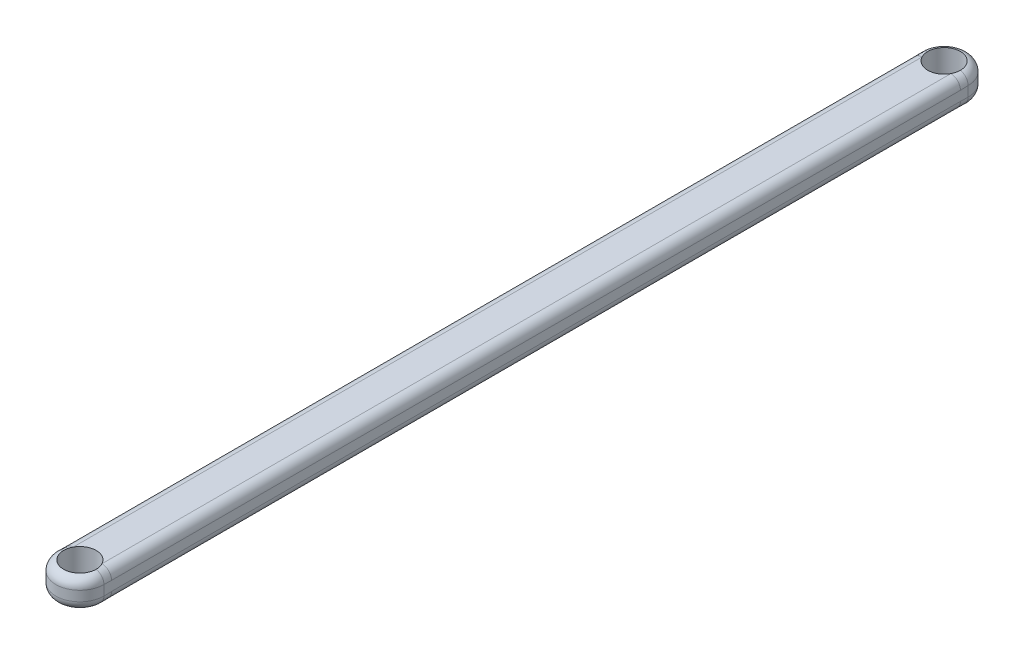
SolidWorks part; units mm, degrees
ref_plane "前视基准面" through (0, 0, 0) normal (0, 0, 1) x (1, 0, 0)
ref_plane "上视基准面" through (0, 0, 0) normal (0, 1, 0) x (1, 0, 0)
ref_plane "右视基准面" through (0, 0, 0) normal (1, 0, 0) x (0, 0, -1)
other "Configuration Table"
sketch "草图1" plane through (0, 0, 0) normal (0, 1, 0) x (1, 0, 0)
  line L0 (0, 0) -> (0, 90)
  line L1 (-2.5, 90) -> (-2.5, 0)
  line L2 (2.5, 0) -> (2.5, 90)
  circle A0 centre (0, 0) radius 2.5
  circle A1 centre (0, 90) radius 2.5
  dimension "D1" = 5
extrude "凸台-拉伸1" add sketch "草图1" along normal blind 3
sketch "草图2" plane through (0, 3, 0) normal (0, 1, 0) x (1, 0, 0)
  line L0 (2.5, 0) -> (2.5, 90) construction
  line L1 (-2.5, 90) -> (-2.5, 0) construction
  line L2 (0, 0) -> (0, 90) construction
  line L3 (2.5, 0) -> (2.5, 90)
  line L4 (-2.5, 90) -> (-2.5, 0)
  line L5 (0, 0) -> (0, 90)
  circle A0 centre (0, 0) radius 1.7
  circle A1 centre (0, 90) radius 2.5
  circle A2 centre (0, 90) radius 2.5
  circle A3 centre (0, 0) radius 2.5
  circle A4 centre (0, 0) radius 2.5
  circle A5 centre (0, 90) radius 1.7
  dimension "D1" = 0
  dimension "D2" = 0
extrude "切除-拉伸1" cut sketch "草图2" against normal up to next
fillet "圆角1" radius 1 4 edges at (-2.5, 0, -45) (-2.5, 3, -45) (2.5, 0, -45) (2.5, 3, -45)
